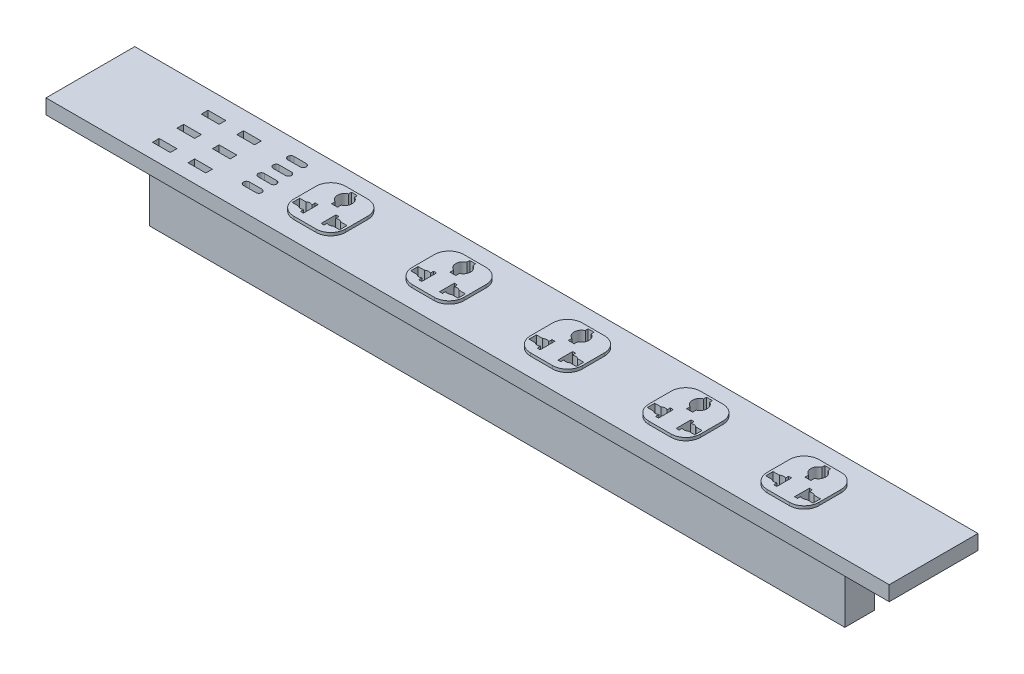
SolidWorks part; units mm, degrees
ref_plane "Front Plane" through (0, 0, 0) normal (0, 0, 1) x (1, 0, 0)
ref_plane "Top Plane" through (0, 0, 0) normal (0, 1, 0) x (1, 0, 0)
ref_plane "Right Plane" through (0, 0, 0) normal (1, 0, 0) x (0, 0, -1)
sketch "Sketch1" plane through (0, 0, 0) normal (0, 1, 0) x (1, 0, 0)
  line L1 (235, -30) -> (-235, -30)
  line L2 (235, -30) -> (235, 30)
  line L3 (235, 30) -> (-235, 30)
  line L4 (-235, -30) -> (-235, 30)
  line L5 (235, -30) -> (-235, 30) construction
  line L6 (235, 30) -> (-235, -30) construction
  point P0 (0, 0)
  dimension "D1" = 60
  dimension "D2" = 470
extrude "Boss-Extrude1" add sketch "Sketch1" along normal blind 10
sketch "Sketch2" plane through (0, 0, 0) normal (0, -1, 0) x (1, 0, 0)
  line L0 (-235, -30) -> (-235, 30) construction
  line L1 (-235, 10) -> (235, 10)
  line L2 (-235, 10) -> (-235, -10)
  line L3 (-235, -10) -> (235, -10)
  line L4 (235, 10) -> (235, -10)
  line L5 (235, 30) -> (235, -30) construction
  line L6 (-235, 30) -> (235, 30) construction
  dimension "D1" = 20
  dimension "D2" = 20
extrude "Boss-Extrude2" add sketch "Sketch2" along normal blind 50
sketch "Sketch3" plane through (0, 10, 0) normal (0, 1, 0) x (1, 0, 0)
  line L1 (215, 17.5) -> (180, 17.5)
  line L2 (215, 17.5) -> (215, -17.5)
  line L3 (215, -17.5) -> (180, -17.5)
  line L4 (180, 17.5) -> (180, -17.5)
  line L5 (235, -30) -> (235, 30) construction
  line L6 (-235, -30) -> (235, -30) construction
  dimension "D1" = 35
  dimension "D2" = 35
  dimension "D3" = 20
  dimension "D4" = 12.5
extrude "Boss-Extrude3" add sketch "Sketch3" along normal blind 2
fillet "Fillet1" radius 10 4 edges at (180, 11, -17.5) (180, 11, 17.5) (215, 11, 17.5) (215, 11, -17.5)
sketch "Sketch5" plane through (0, 12, 0) normal (0, 1, 0) x (1, 0, 0)
  line L0 (190, -17.5) -> (205, -17.5) construction
  line L1 (203.5, -2.5) -> (205.5, -2.5)
  line L2 (203.5, -2.5) -> (203.5, -12.5)
  line L3 (203.5, -12.5) -> (205.5, -12.5)
  line L4 (205.5, -2.5) -> (205.5, -4.6982)
  line L5 (209.2235, -5) -> (213.5, -5)
  line L7 (209.2235, -10) -> (213.5, -10)
  line L8 (213.5, -5) -> (213.5, -10)
  line L9 (197.5, 17.5) -> (197.5, 15.9999) construction
  line L10 (205, 17.5) -> (190, 17.5) construction
  line L11 (189.5, -2.5) -> (189.5, -4.6982)
  line L13 (185.7765, -5) -> (181.5, -5)
  line L14 (181.5, -5) -> (181.5, -10)
  line L15 (185.7765, -10) -> (181.5, -10)
  line L16 (191.5, -12.5) -> (189.5, -12.5)
  line L17 (191.5, -2.5) -> (189.5, -2.5)
  line L18 (191.5, -2.5) -> (191.5, -12.5)
  line L19 (190, -17.5) -> (205, -17.5) construction
  line L21 (196, -1.35) -> (196, -1.3521)
  line L23 (199, -1.35) -> (199, -1.3521)
  line L25 (195.5275, 4.9055) -> (195.5275, 2.5)
  line L26 (205.5, -10.3018) -> (205.5, -12.5)
  line L31 (189.5, -10.3018) -> (189.5, -12.5)
  line L32 (195.5275, 2.5) -> (199.5275, 2.5)
  line L33 (199.5275, 4.9295) -> (199.5275, 2.5)
  line L34 (196.794, 4.5501) -> (199.5275, 2.5) construction
  line L35 (195.5275, 2.5) -> (197.5275, 4) construction
  line L36 (215, -7.5) -> (215, 7.5) construction
  line L37 (180, 7.5) -> (180, -7.5) construction
  line L39 (195.47, 15.9999) -> (199.47, 15.9999)
  line L40 (195.47, 15.9999) -> (195.47, 14.0694)
  line L42 (199.47, 15.9999) -> (199.47, 14.0955)
  line L43 (197.47, 14.4999) -> (197.5, 14.4774) construction
  line L44 (197.47, 14.4999) -> (197.5, 14.5224) construction
  line L45 (197.5, 14.5224) -> (197.5, 14.4774) construction
  arc A2 (209.2235, -5) -> (205.5, -4.6982) centre (207.1469, -7.5) ccw
  arc A3 (189.5, -10.3018) -> (185.7765, -10) centre (187.8531, -7.5) cw
  arc A9 (205.5, -10.3018) -> (209.2235, -10) centre (207.1469, -7.5) ccw
  arc A10 (185.7765, -5) -> (189.5, -4.6982) centre (187.8531, -7.5) cw
  arc A11 (199.5275, 4.9295) -> (199.47, 14.0955) centre (197.5, 9.5) ccw
  arc A12 (197.5, 14.5) -> (197.47, 14.4999) centre (197.5, 9.5) ccw
  arc A13 (195.47, 14.0694) -> (195.5275, 4.9055) centre (197.5, 9.5) ccw
  point P13 (197.5275, 4)
  point P16 (204.5, -12.5)
  point P27 (197.47, 14.4999)
  point P33 (197.5, -1.925)
  point P40 (195.5275, 3.7028)
  point P42 (197.5, 11.575)
  dimension "D2" = 2
  dimension "D11" = 6.5
  dimension "D12" = 6.5
  dimension "D15" = 4
  dimension "D17" = 15.5275
  dimension "D18" = 10
  dimension "D19" = 8
  dimension "D20" = 27
  dimension "D1" = 10
  dimension "D3" = 5
  dimension "D4" = 10
  dimension "D5" = 5
  dimension "D6" = 2.5
  dimension "D7" = 20
  dimension "D8" = 5
  dimension "D9" = 12
  dimension "D10" = 6
  dimension "D13" = 19.2938
  dimension "D14" = 4
  dimension "D16" = 15.4725
  dimension "D21" = 5
extrude "Cut-Extrude1" cut sketch "Sketch5" against normal blind 10 contours A11 L42 L39 L40 A13 L25 L32 L33 | A2 L4 L1 L2 L3 L26 A9 L7 L8 L5 | L18 L16 L31 A3 L15 L14 L13 A10 L11 L17
pattern_linear "LPattern1" count 5 spacing 80 along (-1, 0, 0) of "Boss-Extrude3", "Fillet1", "Cut-Extrude1"
sketch "Sketch7" plane through (0, 10, 0) normal (0, 1, 0) x (1, 0, 0)
  line L0 (-167, 17.5) -> (-158.6, 17.5) construction
  line L1 (-223, 17.5) -> (-211, 17.5)
  line L2 (-223, 17.5) -> (-223, 13)
  line L3 (-223, 13) -> (-211, 13)
  line L4 (-211, 17.5) -> (-211, 13)
  line L5 (-223, 17.5) -> (-211, 13) construction
  line L6 (-223, 13) -> (-211, 17.5) construction
  line L7 (-223, 1) -> (-211, 1)
  line L8 (-223, 1) -> (-223, -3.5)
  line L9 (-223, -3.5) -> (-211, -3.5)
  line L10 (-211, 1) -> (-211, -3.5)
  line L11 (-223, 1) -> (-211, -3.5) construction
  line L12 (-223, -3.5) -> (-211, 1) construction
  line L13 (-223, -15.5) -> (-211, -15.5)
  line L14 (-223, -15.5) -> (-223, -20)
  line L15 (-223, -20) -> (-211, -20)
  line L16 (-211, -15.5) -> (-211, -20)
  line L17 (-223, -15.5) -> (-211, -20) construction
  line L18 (-223, -20) -> (-211, -15.5) construction
  line L19 (-199, 17.5) -> (-187, 17.5)
  line L20 (-199, 17.5) -> (-199, 13)
  line L21 (-199, 13) -> (-187, 13)
  line L22 (-187, 17.5) -> (-187, 13)
  line L23 (-199, 17.5) -> (-187, 13) construction
  line L24 (-199, 13) -> (-187, 17.5) construction
  line L25 (-199, 1) -> (-187, 1)
  line L26 (-199, 1) -> (-199, -3.5)
  line L27 (-199, -3.5) -> (-187, -3.5)
  line L28 (-187, 1) -> (-187, -3.5)
  line L29 (-199, 1) -> (-187, -3.5) construction
  line L30 (-199, -3.5) -> (-187, 1) construction
  line L31 (-199, -15.5) -> (-187, -15.5)
  line L32 (-199, -15.5) -> (-199, -20)
  line L33 (-199, -20) -> (-187, -20)
  line L34 (-187, -15.5) -> (-187, -20)
  line L35 (-199, -15.5) -> (-187, -20) construction
  line L36 (-199, -20) -> (-187, -15.5) construction
  line L37 (-167, 19.5377) -> (-158.6, 19.5377)
  line L38 (-167, 15.4623) -> (-158.6, 15.4623)
  line L39 (-167, 7.5) -> (-158.6, 7.5) construction
  line L42 (-235, -30) -> (235, -30) construction
  line L43 (-235, 30) -> (-235, -30) construction
  line L44 (-167, 9.5377) -> (-158.6, 9.5377)
  line L45 (-167, 5.4623) -> (-158.6, 5.4623)
  line L46 (-167, -2.5) -> (-158.6, -2.5) construction
  line L47 (-167, -0.4623) -> (-158.6, -0.4623)
  line L48 (-167, -4.5377) -> (-158.6, -4.5377)
  line L49 (-167, -12.5) -> (-158.6, -12.5) construction
  line L50 (-167, -10.4623) -> (-158.6, -10.4623)
  line L51 (-167, -14.5377) -> (-158.6, -14.5377)
  line L52 (-167, 17.5) -> (-167, 7.5) construction
  arc A0 (-167, 19.5377) -> (-167, 15.4623) centre (-167, 17.5) ccw
  arc A1 (-158.6, 15.4623) -> (-158.6, 19.5377) centre (-158.6, 17.5) ccw
  arc A4 (-167, 9.5377) -> (-167, 5.4623) centre (-167, 7.5) ccw
  arc A5 (-158.6, 5.4623) -> (-158.6, 9.5377) centre (-158.6, 7.5) ccw
  arc A6 (-167, -0.4623) -> (-167, -4.5377) centre (-167, -2.5) ccw
  arc A7 (-158.6, -4.5377) -> (-158.6, -0.4623) centre (-158.6, -2.5) ccw
  arc A8 (-167, -10.4623) -> (-167, -14.5377) centre (-167, -12.5) ccw
  arc A9 (-158.6, -14.5377) -> (-158.6, -10.4623) centre (-158.6, -12.5) ccw
  point P0 (-217, 15.25)
  point P5 (-217, -1.25)
  point P10 (-217, -17.75)
  point P15 (-193, 15.25)
  point P20 (-193, -1.25)
  point P25 (-193, -17.75)
  point P32 (-162.8, 17.5)
  point P41 (-162.8, 7.5)
  point P52 (-162.8, -2.5)
  point P59 (-162.8, -12.5)
  dimension "D1" = 12
  dimension "D2" = 4.5
  dimension "D3" = 12
  dimension "D4" = 12
  dimension "D5" = 4.5
  dimension "D6" = 4.5
  dimension "D7" = 12
  dimension "D8" = 12
  dimension "D9" = 10
  dimension "D10" = 12
  dimension "D11" = 12
  dimension "D12" = 12
  dimension "D13" = 12
  dimension "D14" = 4.5
  dimension "D15" = 4.5
  dimension "D16" = 4.5
  dimension "D17" = 12
  dimension "D18" = 12
  dimension "D19" = 12
  dimension "D20" = 12
  dimension "D21" = 12
  dimension "D22" = 10
  dimension "D23" = 12
  dimension "D24" = 12
  dimension "D25" = 12
  dimension "D26" = 8.4
  dimension "D27" = 4.0753
  dimension "D28" = 20
  dimension "D30" = 10
  dimension "D29" = 4
extrude "Cut-Extrude2" cut sketch "Sketch7" against normal blind 10
sketch "Sketch8" plane through (235, 0, 0) normal (1, 0, 0) x (0, 0, -1)
  line L0 (-30, 10) -> (-30, 0) construction
  line L1 (-30, 0) -> (-10, 0) construction
  line L2 (10, 0) -> (30, 0) construction
  line L3 (30, 10) -> (30, 0) construction
  line L4 (-30, 10) -> (30, 10) construction
  line L5 (-30, 10) -> (-30, 0)
  line L6 (-30, 0) -> (-10, 0)
  line L7 (10, 0) -> (30, 0)
  line L8 (30, 10) -> (30, 0)
  line L9 (-30, 10) -> (30, 10)
  line L10 (-10, 0) -> (10, 0)
extrude "Boss-Extrude4" add sketch "Sketch8" along normal blind 50
sketch "Sketch9" plane through (-235, 0, 0) normal (-1, 0, 0) x (0, 0, 1)
  line L1 (-30, 10) -> (30, 10)
  line L2 (-30, 10) -> (-30, 0)
  line L3 (-30, 0) -> (30, 0)
  line L4 (30, 10) -> (30, 0)
extrude "Boss-Extrude5" add sketch "Sketch9" along normal blind 50
